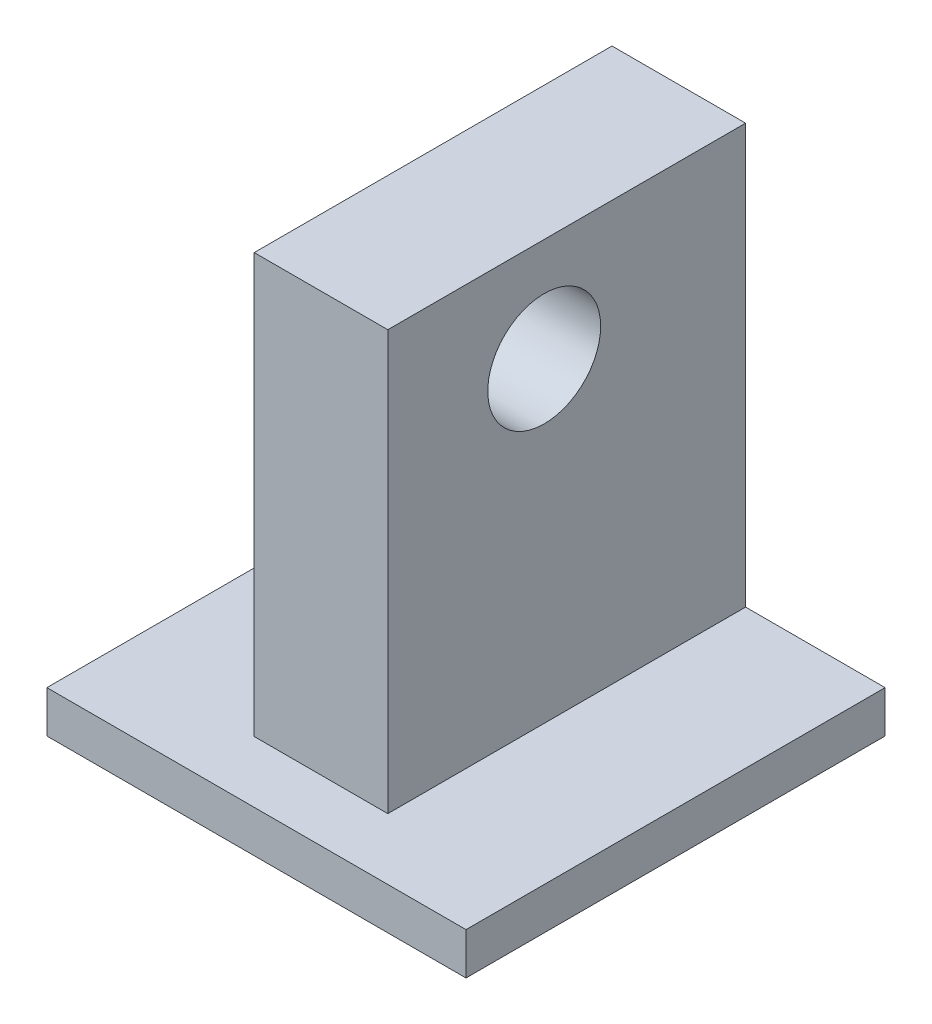
SolidWorks part; units mm, degrees
ref_plane "Alzado" through (0, 0, 0) normal (0, 0, 1) x (1, 0, 0)
ref_plane "Planta" through (0, 0, 0) normal (0, 1, 0) x (1, 0, 0)
ref_plane "Vista lateral" through (0, 0, 0) normal (1, 0, 0) x (0, 0, -1)
sketch "Croquis1" plane through (0, 0, 0) normal (0, 1, 0) x (1, 0, 0)
  line L1 (-15, 15) -> (15, 15)
  line L2 (-15, 15) -> (-15, -15)
  line L3 (-15, -15) -> (15, -15)
  line L4 (15, 15) -> (15, -15)
  line L5 (-15, 15) -> (15, -15) construction
  line L6 (-15, -15) -> (15, 15) construction
  point P0 (0, 0)
  dimension "D1" = 30
  dimension "D2" = 30
extrude "Saliente-Extruir1" add sketch "Croquis1" along normal blind 3
sketch "Croquis2" plane through (0, 3, 0) normal (0, 1, 0) x (1, 0, 0)
  line L0 (15, 15) -> (-15, 15) construction
  line L1 (-4.5492, 15) -> (5.0139, 15)
  line L2 (-4.5492, 15) -> (-4.5492, -10.6107)
  line L3 (-4.5492, -10.6107) -> (5.0139, -10.6107)
  line L4 (5.0139, 15) -> (5.0139, -10.6107)
extrude "Saliente-Extruir2" add sketch "Croquis2" along normal blind 30
sketch "Croquis3" plane through (5.0139, 0, 0) normal (1, 0, 0) x (0, 0, -1)
  circle A0 centre (0.5847, 25.6037) radius 4.0394
extrude "Cortar-Extruir1" cut sketch "Croquis3" against normal blind 10
